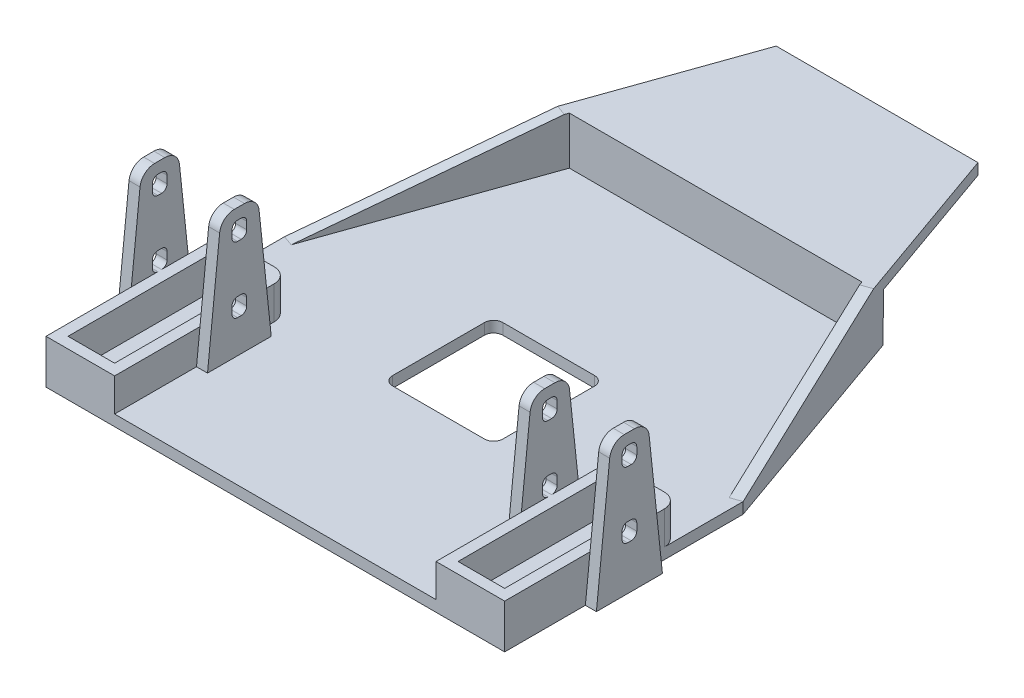
SolidWorks part; units mm, degrees
ref_plane "Plano frontal" through (0, 0, 0) normal (0, 0, 1) x (1, 0, 0)
ref_plane "Plano superior" through (0, 0, 0) normal (0, 1, 0) x (1, 0, 0)
ref_plane "Plano direito" through (0, 0, 0) normal (1, 0, 0) x (0, 0, -1)
sketch "Esboço1" plane through (0, 0, 0) normal (0, 1, 0) x (1, 0, 0)
  line L1 (-62.5, 62) -> (62.5, 62)
  line L2 (-62.5, 62) -> (-62.5, -62)
  line L3 (-62.5, -62) -> (62.5, -62)
  line L4 (62.5, 62) -> (62.5, -62)
  line L5 (-62.5, 62) -> (62.5, -62) construction
  line L6 (-62.5, -62) -> (62.5, 62) construction
  point P0 (0, 0)
  dimension "D1" = 125
  dimension "D2" = 124
extrude "Extrusão1" add sketch "Esboço1" along normal blind 3
sketch "Esboço2" plane through (0, 3, 0) normal (0, 1, 0) x (1, 0, 0)
  line L0 (-62.5, -26) -> (-62.5, -14.5)
  line L1 (-62.5, -62) -> (-43.8, -62)
  line L2 (-62.5, -62) -> (-62.5, -36)
  line L3 (-62.5, -14.5) -> (-43.8, -14.5)
  line L4 (-43.8, -62) -> (-43.8, -14.5)
  line L5 (-62.5, -26) -> (-62.5, -36)
  line L9 (-59.5, -59) -> (-46.8, -59)
  line L10 (-59.5, -59) -> (-59.5, -17.5)
  line L11 (-59.5, -17.5) -> (-46.8, -17.5)
  line L12 (-46.8, -59) -> (-46.8, -17.5)
  dimension "D1" = 47.5
  dimension "D2" = 18.7
  dimension "D6" = 3
  dimension "D7" = 3
  dimension "D8" = 3
  dimension "D9" = 3
extrude "Extrusão2" add sketch "Esboço2" along normal blind 9
fillet "Filete1" radius 4 2 edges at (-43.8, 7.5, 14.5)
fillet "Filete2" radius 2 2 edges at (-59.5, 7.5, 17.5) (-46.8, 7.5, 17.5)
mirror "Espelhar3" about plane through (0, 0, 0) normal (1, 0, 0) of "Extrusão2"
fillet "Filete3" radius 4 2 edges at (43.8, 7.5, 14.5) (62.5, 7.5, 14.5)
fillet "Filete4" radius 2 2 edges at (59.5, 7.5, 17.5) (46.8, 7.5, 17.5)
sketch "Esboço3" plane through (0, 3, 0) normal (0, 1, 0) x (1, 0, 0)
  line L0 (-62.5, -18.5) -> (-62.5, -62) construction
  line L1 (-62.5, -36) -> (-65.5, -36)
  line L2 (-62.5, -36) -> (-62.5, -26)
  line L3 (-62.5, -26) -> (-65.5, -26)
  line L4 (-65.5, -36) -> (-65.5, -26)
  line L5 (-62.5, -62) -> (-43.8, -62) construction
  line L6 (-43.8, -62) -> (-43.8, -18.5) construction
  line L7 (-43.8, -36) -> (-40.8, -36)
  line L8 (-43.8, -36) -> (-43.8, -26)
  line L9 (-43.8, -26) -> (-40.8, -26)
  line L10 (-40.8, -36) -> (-40.8, -26)
  dimension "D1" = 26
  dimension "D2" = 10
  dimension "D3" = 3
  dimension "D4" = 3
  dimension "D5" = 26
  dimension "D6" = 10
extrude "Extrusão4" add sketch "Esboço3" along normal blind 35 and the other way blind 3
mirror "Espelhar6" about plane through (0, 0, 0) normal (1, 0, 0) of "Extrusão4"
sketch "Esboço5" plane through (-65.5, 0, 0) normal (-1, 0, 0) x (0, 0, 1)
  line L0 (26, 0) -> (36, 0) construction
  line L1 (30.5, 12) -> (31.5, 12)
  line L2 (29, 13.5) -> (29, 15.5)
  line L3 (30.5, 17) -> (31.5, 17)
  line L4 (33, 13.5) -> (33, 15.5)
  line L5 (36, 0) -> (36, 38) construction
  arc A0 (29, 15.5) -> (30.5, 17) centre (30.5, 15.5) cw
  arc A1 (31.5, 17) -> (33, 15.5) centre (31.5, 15.5) cw
  arc A2 (30.5, 12) -> (29, 13.5) centre (30.5, 13.5) cw
  arc A3 (31.5, 12) -> (33, 13.5) centre (31.5, 13.5) ccw
  point P10 (29, 17)
  point P15 (29, 12)
  point P18 (33, 12)
  dimension "D5" = 1.5
  dimension "D1" = 12
  dimension "D2" = 5
  dimension "D3" = 3
  dimension "D4" = 4
extrude "Extrusão5" cut sketch "Esboço5" against normal through all
sketch "Esboço6" plane through (-65.5, 0, 0) normal (-1, 0, 0) x (0, 0, 1)
  line L0 (26, 0) -> (36, 0) construction
  line L1 (30.5, 30) -> (31.5, 30)
  line L2 (29, 31.5) -> (29, 33.5)
  line L3 (30.5, 35) -> (31.5, 35)
  line L4 (33, 31.5) -> (33, 33.5)
  line L6 (36, 0) -> (36, 38) construction
  arc A0 (29, 33.5) -> (30.5, 35) centre (30.5, 33.5) cw
  arc A1 (30.5, 30) -> (29, 31.5) centre (30.5, 31.5) cw
  arc A2 (31.5, 30) -> (33, 31.5) centre (31.5, 31.5) ccw
  arc A3 (31.5, 35) -> (33, 33.5) centre (31.5, 33.5) cw
  point P10 (29, 35)
  point P13 (29, 30)
  point P16 (33, 30)
  dimension "D5" = 1.5
  dimension "D1" = 30
  dimension "D2" = 5
  dimension "D3" = 4
  dimension "D4" = 3
extrude "Extrusão6" cut sketch "Esboço6" against normal through all
sketch "Esboço7" plane through (-65.5, 0, 0) normal (-1, 0, 0) x (0, 0, 1)
  line L0 (26, 0) -> (22, 0)
  line L1 (-62, 0) -> (26, 0) construction
  line L2 (22, 0) -> (26, 38)
  line L3 (26, 38) -> (26, 0)
  line L6 (36, 38) -> (36, 0)
  line L7 (36, 0) -> (40, 0)
  line L8 (36, 0) -> (62, 0) construction
  line L9 (40, 0) -> (36, 38)
  dimension "D1" = 4
  dimension "D2" = 4
extrude "Extrusão7" add sketch "Esboço7" against normal blind 3
sketch "Esboço8" plane through (-43.8, 0, 0) normal (-1, 0, 0) x (0, 0, 1)
  line L0 (26, 38) -> (22, 0)
  line L1 (22, 0) -> (26, 0)
  line L2 (22, 0) -> (40, 0) construction
  line L3 (26, 0) -> (26, 38)
  line L4 (36, 38) -> (36, 0)
  line L5 (36, 0) -> (40, 0)
  line L6 (40, 0) -> (36, 38)
extrude "Extrusão8" add sketch "Esboço8" against normal blind 3
fillet "Filete5" radius 4 4 edges at (-42.3, 38, 36) (-42.3, 38, 26) (-64, 38, 36) (-64, 38, 26)
mirror "Espelhar9" about plane through (0, 0, 0) normal (1, 0, 0) of "Extrusão8", "Extrusão7"
fillet "Filete6" radius 4 4 edges at (64, 38, 26) (42.3, 38, 26) (64, 38, 36) (42.3, 38, 36)
sketch "Esboço9" plane through (0, 3, 0) normal (0, 1, 0) x (1, 0, 0)
  line L12 (-12.5, -17.5) -> (12.5, -17.5)
  line L13 (-15, -15) -> (-15, 10)
  line L14 (-12.5, 12.5) -> (12.5, 12.5)
  line L15 (15, -15) -> (15, 10)
  arc A0 (-15, 10) -> (-12.5, 12.5) centre (-12.5, 10) cw
  arc A1 (-12.5, -17.5) -> (-15, -15) centre (-12.5, -15) cw
  arc A2 (12.5, -17.5) -> (15, -15) centre (12.5, -15) ccw
  arc A3 (12.5, 12.5) -> (15, 10) centre (12.5, 10) cw
  point P10 (-15, 12.5)
  point P17 (-15, -17.5)
  point P20 (15, -17.5)
  dimension "D8" = 2.5
  dimension "D4" = 30
  dimension "D5" = 30
extrude "Extrusão9" cut sketch "Esboço9" against normal blind 3
sketch "Esboço10" plane through (0, 3, 0) normal (0, 1, 0) x (1, 0, 0)
  line L0 (62.5, -18.5) -> (62.5, 62) construction
  line L1 (-62.5, 62) -> (62.5, 62)
  line L2 (-62.5, 62) -> (-62.5, 58)
  line L3 (-62.5, 58) -> (62.5, 58)
  line L4 (62.5, 62) -> (62.5, 58)
  dimension "D1" = 4
extrude "Extrusão10" add sketch "Esboço10" along normal blind 13
sketch "Esboço11" plane through (0, 0, -62) normal (0, 0, -1) x (-1, 0, 0)
  line L0 (62.5, 16) -> (62.5, 0) construction
  line L1 (-62.5, 16) -> (62.5, 16)
  line L2 (-62.5, 16) -> (-62.5, 13)
  line L3 (-62.5, 13) -> (62.5, 13)
  line L4 (62.5, 16) -> (62.5, 13)
  dimension "D1" = 3
extrude "Extrusão11" add sketch "Esboço11" along normal blind 40
sketch "Esboço13" plane through (0, 3, 0) normal (0, 1, 0) x (1, 0, 0)
  line L0 (-62.5, 3) -> (-27.5, 102)
  line L1 (-62.5, 58) -> (-62.5, -18.5) construction
  line L2 (-62.5, 102) -> (62.5, 102) construction
  line L3 (-27.5, 102) -> (-62.5, 102)
  line L4 (-62.5, 102) -> (-62.5, 3)
  line L5 (27.5, 102) -> (62.5, 102)
  line L6 (62.5, 102) -> (62.5, 3)
  line L7 (62.5, -18.5) -> (62.5, 58) construction
  line L8 (62.5, 3) -> (27.5, 102)
  dimension "D1" = 55
  dimension "D2" = 35
  dimension "D3" = 65
  dimension "D4" = 65
extrude "Extrusão12" cut sketch "Esboço13" against normal blind 40 and the other way blind 40
sketch "Esboço15" plane through (56.499, 0, -19.9744) normal (0.9428, 0, -0.3333) x (-0.3333, 0, -0.9428)
  line L0 (44.7238, 16) -> (40.332, 16)
  line L1 (40.332, 16) -> (87.0008, 16) construction
  line L2 (40.332, 16) -> (-18.0039, 3)
  line L3 (-18.0039, 3) -> (-18.0039, 0)
  line L4 (-18.0039, 3) -> (-18.0039, 0) construction
  line L5 (-41.5743, 0) -> (-18.0039, 0) construction
  line L6 (-18.0039, 0) -> (44.5746, 0)
  line L7 (-18.0039, 0) -> (44.5746, 0) construction
  line L8 (44.5746, 0) -> (44.7238, 16)
extrude "Extrusão18" add sketch "Esboço15" against normal blind 3
mirror "Espelhar10" about plane through (0, 0, 0) normal (1, 0, 0) of "Extrusão18"
sketch "Esboço16" plane through (0, 0, 0) normal (0, -1, 0) x (1, 0, 0)
  circle A0 centre (-12, 52) radius 5.25
  circle A1 centre (12, 52) radius 5.25
  circle A2 centre (-12, -47) radius 5.25
  circle A3 centre (12, -47) radius 5.25
  dimension "D12" = 10.5
  dimension "D13" = 10.5
  dimension "D14" = 10.5
  dimension "D15" = 10.5
extrude "Extrusão19" cut sketch "Esboço16" against normal blind 2
